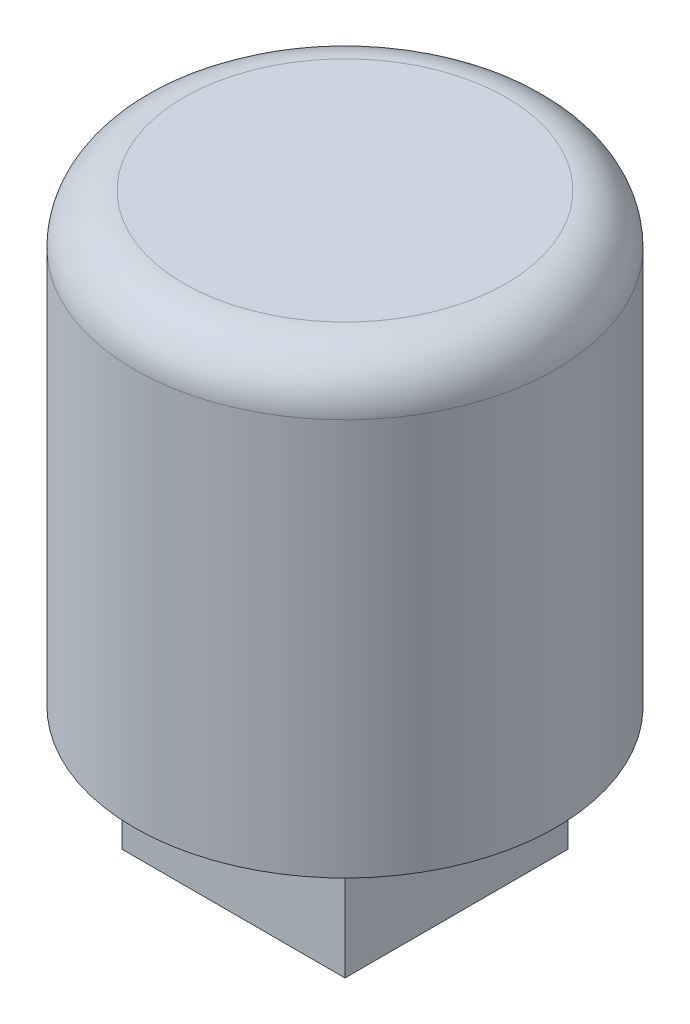
SolidWorks part; units mm, degrees
ref_plane "Front Plane" through (0, 0, 0) normal (0, 0, 1) x (1, 0, 0)
ref_plane "Top Plane" through (0, 0, 0) normal (0, 1, 0) x (1, 0, 0)
ref_plane "Right Plane" through (0, 0, 0) normal (1, 0, 0) x (0, 0, -1)
sketch "Sketch1" plane through (0, 0, 0) normal (0, 1, 0) x (1, 0, 0)
  circle A0 centre (0, 0) radius 85
extrude "Boss-Extrude2" add sketch "Sketch1" along normal blind 180
sketch "Sketch2" plane through (0, 0, 0) normal (0, -1, 0) x (1, 0, 0)
  line L1 (45, 45) -> (-45, 45)
  line L2 (45, 45) -> (45, -45)
  line L3 (45, -45) -> (-45, -45)
  line L4 (-45, 45) -> (-45, -45)
  line L5 (45, 45) -> (-45, -45) construction
  line L6 (45, -45) -> (-45, 45) construction
  point P0 (0, 0)
extrude "Boss-Extrude3" add sketch "Sketch2" along normal blind 50
fillet "Fillet1" radius 20 1 edges at (0, 180, 85)
